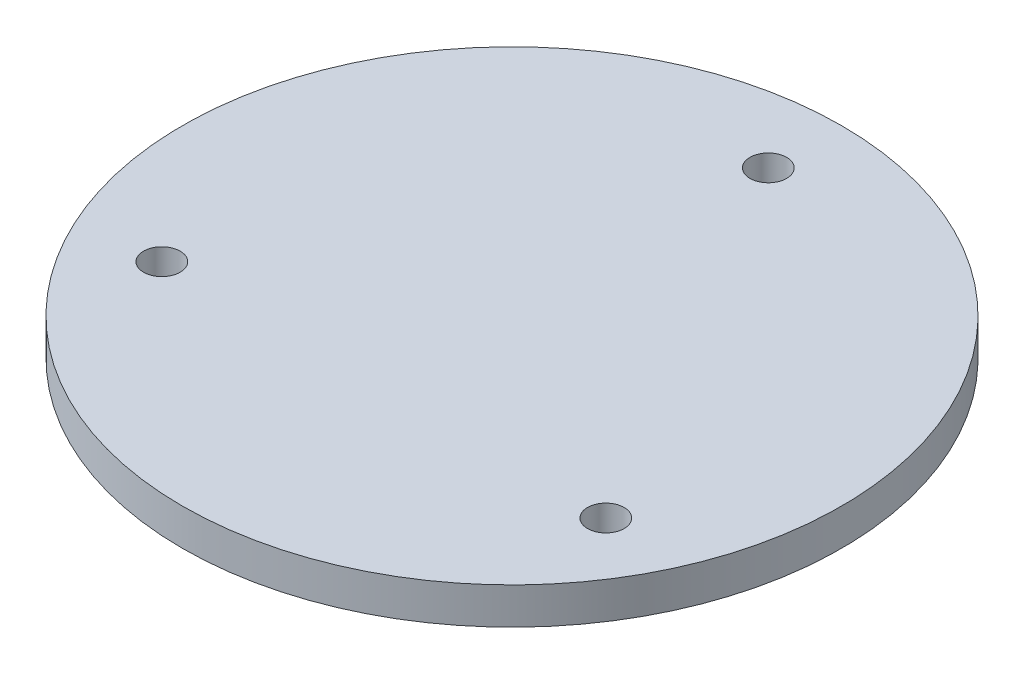
SolidWorks part; units mm, degrees
ref_plane "Front Plane" through (0, 0, 0) normal (0, 0, 1) x (1, 0, 0)
ref_plane "Top Plane" through (0, 0, 0) normal (0, 1, 0) x (1, 0, 0)
ref_plane "Right Plane" through (0, 0, 0) normal (1, 0, 0) x (0, 0, -1)
sketch "Sketch1" plane through (0, 0, 0) normal (0, 1, 0) x (1, 0, 0)
  circle A0 centre (0, 0) radius 114.3
  circle A1 centre (0, 88.9) radius 6.35
  circle A4 centre (76.9897, -44.45) radius 6.35
  circle A5 centre (-76.9897, -44.45) radius 6.35
  point P11 (0, 0)
  dimension "D1" = 228.6
  dimension "D2" = 12.7
  dimension "D3" = 88.9
  dimension "D4" = 3
extrude "Boss-Extrude1" add sketch "Sketch1" along normal blind 12.7
